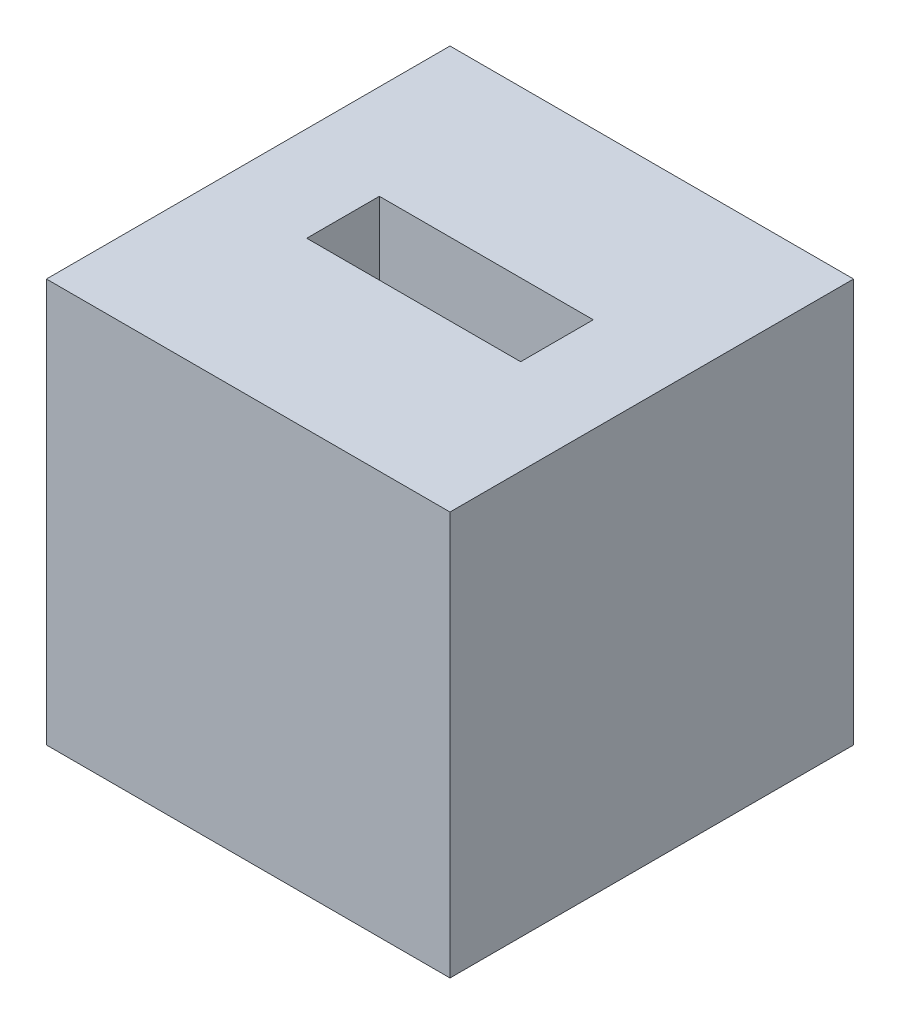
SolidWorks part; units mm, degrees
ref_plane "前视基准面" through (0, 0, 0) normal (0, 0, 1) x (1, 0, 0)
ref_plane "上视基准面" through (0, 0, 0) normal (0, 1, 0) x (1, 0, 0)
ref_plane "右视基准面" through (0, 0, 0) normal (1, 0, 0) x (0, 0, -1)
other "Configuration Table"
sketch "草图1" plane through (0, 0, 0) normal (0, 1, 0) x (1, 0, 0)
  line L1 (-5, 5) -> (5, 5)
  line L2 (-5, 5) -> (-5, -5)
  line L3 (-5, -5) -> (5, -5)
  line L4 (5, 5) -> (5, -5)
  line L5 (-5, 5) -> (5, -5) construction
  line L6 (-5, -5) -> (5, 5) construction
  point P0 (0, 0)
  dimension "D1" = 10
  dimension "D2" = 10
extrude "凸台-拉伸1" add sketch "草图1" along normal blind 10
sketch "草图2" plane through (0, 10, 0) normal (0, 1, 0) x (1, 0, 0)
  line L1 (-2.65, 0.9) -> (2.65, 0.9)
  line L2 (-2.65, 0.9) -> (-2.65, -0.9)
  line L3 (-2.65, -0.9) -> (2.65, -0.9)
  line L4 (2.65, 0.9) -> (2.65, -0.9)
  line L5 (-2.65, 0.9) -> (2.65, -0.9) construction
  line L6 (-2.65, -0.9) -> (2.65, 0.9) construction
  point P0 (0, 0)
  dimension "D1" = 5.3
  dimension "D2" = 1.8
extrude "切除-拉伸1" cut sketch "草图2" against normal through all
